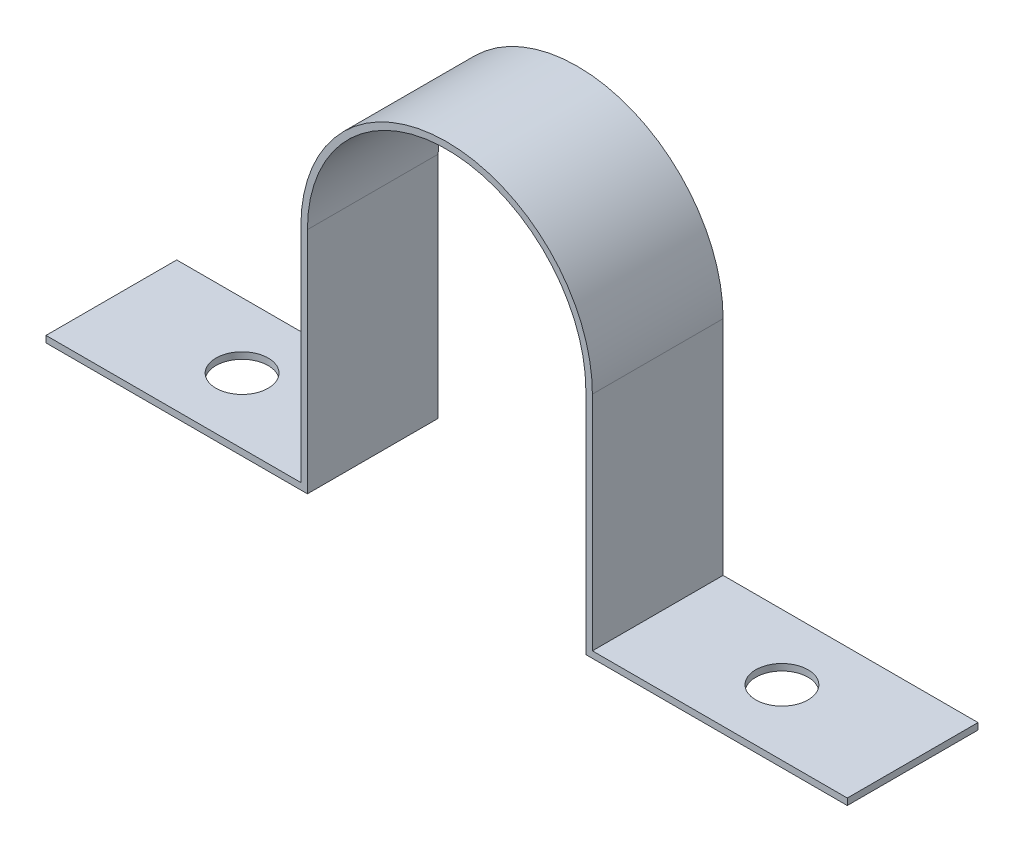
SolidWorks part; units mm, degrees
ref_plane "Alzado" through (0, 0, 0) normal (0, 0, 1) x (1, 0, 0)
ref_plane "Planta" through (0, 0, 0) normal (0, 1, 0) x (1, 0, 0)
ref_plane "Vista lateral" through (0, 0, 0) normal (1, 0, 0) x (0, 0, -1)
sketch "Croquis1" plane through (0, 0, 0) normal (0, 0, 1) x (1, 0, 0)
  line L7 (0, 0) -> (0, -10.2182) construction
  line L12 (-11.15, 0) -> (-11.15, -17.0074)
  line L16 (-10.65, 0) -> (-10.65, -17.5074)
  line L17 (10.65, 17.5074) -> (-10.65, -17.5074) construction
  line L18 (10.65, -17.5074) -> (-10.65, 17.5074) construction
  line L25 (-11.15, 18.0074) -> (-11.15, -18.0074) construction
  line L26 (11.15, -18.0074) -> (-11.15, -18.0074) construction
  line L30 (11.15, 18.0074) -> (11.15, -18.0074) construction
  line L31 (10.65, -17.5074) -> (-10.65, -17.5074) construction
  line L32 (11.15, 18.0074) -> (-11.15, 18.0074) construction
  line L33 (10.65, 17.5074) -> (-10.65, 17.5074) construction
  line L34 (-10.65, 17.5074) -> (-10.65, -17.5074) construction
  line L35 (10.65, 17.5074) -> (10.65, -17.5074) construction
  line L36 (-10.65, -17.5074) -> (-30.65, -17.5074)
  line L37 (-30.65, -17.5074) -> (-30.65, -17.0074)
  line L38 (-30.65, -17.0074) -> (-11.15, -17.0074)
  line L39 (30.65, -17.0074) -> (11.15, -17.0074)
  line L40 (30.65, -17.5074) -> (30.65, -17.0074)
  line L41 (10.65, -17.5074) -> (30.65, -17.5074)
  line L42 (10.65, 0) -> (10.65, -17.5074)
  line L43 (11.15, 0) -> (11.15, -17.0074)
  arc A1 (11.15, 0) -> (-11.15, 0) centre (0, 0) ccw
  arc A4 (10.65, 0) -> (-10.65, 0) centre (0, 0) ccw
  dimension "D1" = 11.15
  dimension "D2" = 0.5
  dimension "D6" = 10.65
  dimension "D3" = 20
  dimension "D5" = 17.5074
  dimension "D7" = 0.5
extrude "Saliente-Extruir1" add sketch "Croquis1" along normal blind 10
sketch "Croquis2" plane through (0, -17.0074, 0) normal (0, 1, 0) x (1, 0, 0)
  line L3 (-30.65, -10) -> (-30.65, 0) construction
  line L4 (0, 0) -> (0, -10) construction
  line L5 (-11.15, -10) -> (11.15, -10) construction
  line L6 (-11.15, -10) -> (-30.65, -10) construction
  circle A0 centre (-20.65, -5) radius 2
  circle A2 centre (20.65, -5) radius 2
  dimension "D1" = 10
  dimension "D3" = 4
  dimension "D2" = 5
extrude "Cortar-Extruir1" cut sketch "Croquis2" against normal blind 10
